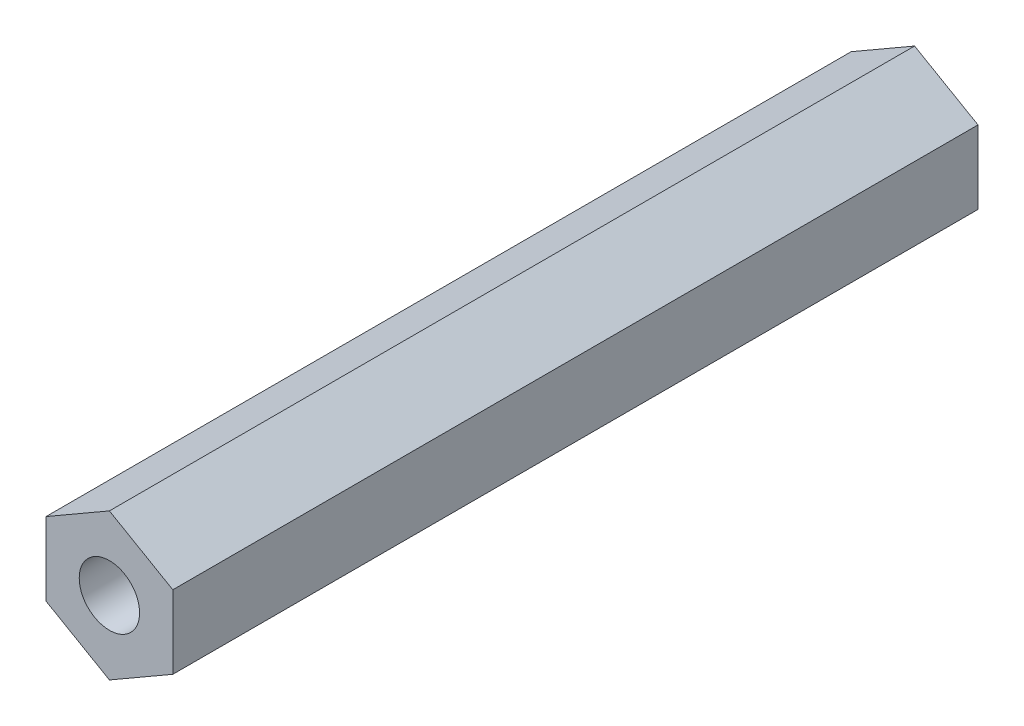
SolidWorks part; units mm, degrees
ref_plane "Plan de face" through (0, 0, 0) normal (0, 0, 1) x (1, 0, 0)
ref_plane "Plan de dessus" through (0, 0, 0) normal (0, 1, 0) x (1, 0, 0)
ref_plane "Plan de droite" through (0, 0, 0) normal (1, 0, 0) x (0, 0, -1)
sketch "Esquisse1" plane through (0, 0, 0) normal (0, 0, 1) x (1, 0, 0)
  line L1 (-2.52, 1.4549) -> (-2.52, -1.4549)
  line L2 (-2.52, -1.4549) -> (0, -2.9098)
  line L3 (0, -2.9098) -> (2.52, -1.4549)
  line L4 (2.52, -1.4549) -> (2.52, 1.4549)
  line L5 (2.52, 1.4549) -> (0, 2.9098)
  line L6 (0, 2.9098) -> (-2.52, 1.4549)
  circle A0 centre (0, 0) radius 2.52 construction
  dimension "D1" = 5.04
  dimension "D2" = 5.04
  dimension "D3" = 5.04
  dimension "D4" = 5.04
extrude "Boss.-Extru.1" add sketch "Esquisse1" along normal blind 32
sketch "Esquisse2" plane through (0, 0, 0) normal (0, 0, -1) x (-1, 0, 0)
  circle A0 centre (0, 0) radius 1.2
  dimension "D1" = 2.4
extrude "Enlèv. mat.-Extru.1" cut sketch "Esquisse2" against normal blind 32
